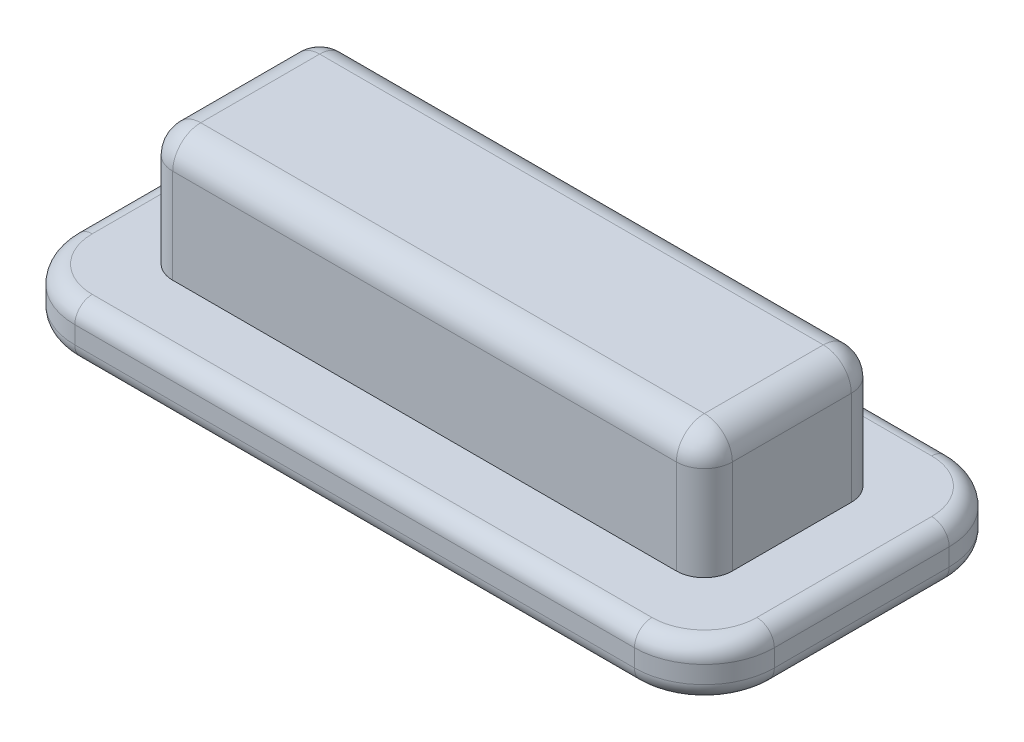
SolidWorks part; units mm, degrees
ref_plane "Front Plane" through (0, 0, 0) normal (0, 0, 1) x (1, 0, 0)
ref_plane "Top Plane" through (0, 0, 0) normal (0, 1, 0) x (1, 0, 0)
ref_plane "Right Plane" through (0, 0, 0) normal (1, 0, 0) x (0, 0, -1)
sketch "Sketch1" plane through (0, 0, 0) normal (0, 1, 0) x (1, 0, 0)
  line L1 (0, 0) -> (8, 0)
  line L2 (0, 0) -> (0, 2.5)
  line L3 (0, 2.5) -> (8, 2.5)
  line L4 (8, 0) -> (8, 2.5)
  dimension "D1" = 2.5
  dimension "D2" = 8
extrude "Boss-Extrude1" add sketch "Sketch1" along normal blind 1.75 contours L2 L1 L4 L3
sketch "Sketch2" plane through (0, 0, 0) normal (0, -1, 0) x (1, 0, 0)
  line L8 (-1, -3.5) -> (9, -3.5)
  line L9 (9, -3.5) -> (9, 1)
  line L10 (9, 1) -> (-1, 1)
  line L11 (-1, 1) -> (-1, -3.5)
  line L12 (-1, -3.5) -> (9, -3.5)
  line L13 (9, -3.5) -> (9, 1)
  line L14 (9, 1) -> (-1, 1)
  line L15 (-1, 1) -> (-1, -3.5)
  dimension "D1" = 1
extrude "Boss-Extrude2" add sketch "Sketch2" along normal blind 0.75
fillet "Fillet1" radius 0.4 4 edges at (8, 0.875, 0) (8, 0.875, -2.5) (0, 0.875, -2.5) (0, 0.875, 0)
fillet "Fillet2" radius 0.4 8 edges at (0.1172, 1.75, -0.1172) (0, 1.75, -1.25) (0.1172, 1.75, -2.3828) (4, 1.75, -2.5) (7.8828, 1.75, -2.3828) (8, 1.75, -1.25) (7.8828, 1.75, -0.1172) (4, 1.75, 0)
fillet "Fillet3" radius 1 4 edges at (9, -0.375, -3.5) (-1, -0.375, -3.5) (-1, -0.375, 1) (9, -0.375, 1)
fillet "Fillet4" radius 0.25 16 edges at (8.7071, -0.75, 0.7071) (9, -0.75, -1.25) (8.7071, -0.75, -3.2071) (4, -0.75, -3.5) (-0.7071, -0.75, -3.2071) (-1, -0.75, -1.25) (-0.7071, -0.75, 0.7071) (8.7071, 0, 0.7071) (9, 0, -1.25) (8.7071, 0, -3.2071) (4, 0, -3.5) (-0.7071, 0, -3.2071) (-1, 0, -1.25) (-0.7071, 0, 0.7071) (4, -0.75, 1) (4, 0, 1)
